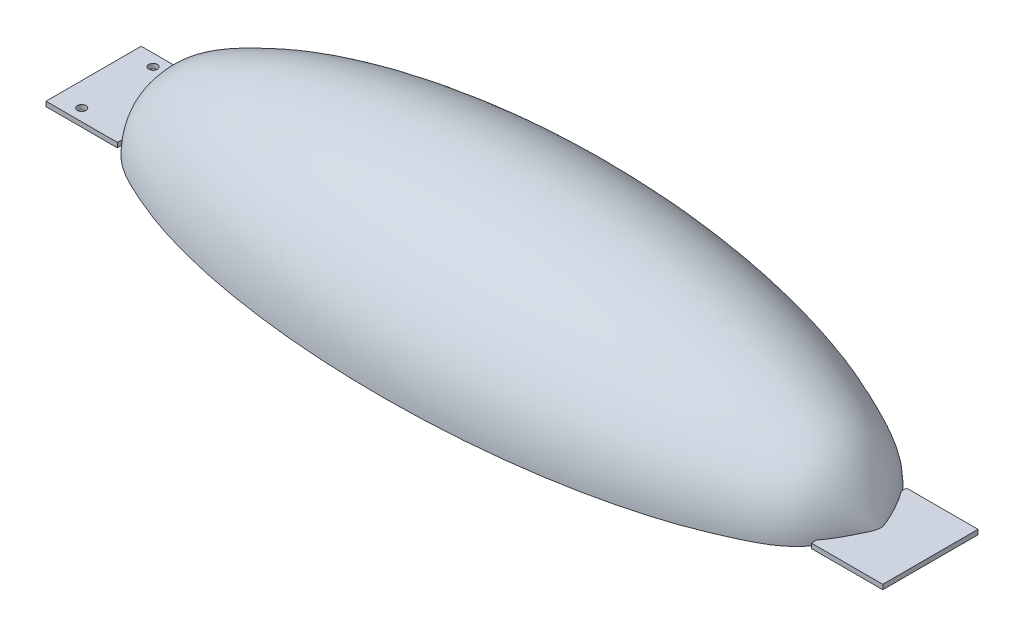
SolidWorks part; units mm, degrees
ref_plane "Front Plane" through (0, 0, 0) normal (0, 0, 1) x (1, 0, 0)
ref_plane "Top Plane" through (0, 0, 0) normal (0, 1, 0) x (1, 0, 0)
ref_plane "Right Plane" through (0, 0, 0) normal (1, 0, 0) x (0, 0, -1)
sketch "Sketch1" plane through (0, 0, 0) normal (0, 0, 1) x (1, 0, 0)
  line L0 (-311.5, 0) -> (0, 0)
  line L1 (10, 0) -> (-321.5, 0) construction
  spline S0 degree 3 poles (0, 0) (-4.2492, 8.9399) (-11.1739, 23.509) (-30.8102, 33.047) (-46.4415, 39.4769) (-62.1775, 44.1339) (-77.7886, 47.7571) (-93.3969, 50.5181) (-108.9899, 52.5683) (-124.5791, 53.9845) (-140.1651, 54.8169) (-155.75, 55.0915) (-171.3349, 54.8169) (-186.9209, 53.9845) (-202.5101, 52.5683) (-218.1031, 50.5181) (-233.7114, 47.7571) (-249.3225, 44.1339) (-265.0585, 39.4769) (-280.6898, 33.047) (-300.3261, 23.509) (-307.2508, 8.9399) (-311.5, 0) knots 0 0 0 0 0.082154 0.133883 0.182139 0.228907 0.274864 0.320327 0.365473 0.410415 0.455236 0.5 0.544764 0.589585 0.634527 0.679673 0.725136 0.771093 0.817861 0.866117 0.917846 1 1 1 1
revolve "Revolve1" add sketch "Sketch1" angle 360 about L1
sketch "Sketch2" plane through (0, 0, 0) normal (0, 1, 0) x (1, 0, 0)
  line L0 (-361.5, 80) -> (50, 80)
  line L1 (50, 80) -> (50, -80)
  line L2 (50, -80) -> (-361.5, -80)
  line L3 (-361.5, -80) -> (-361.5, 80)
extrude "Cut-Extrude1" cut sketch "Sketch2" against normal blind 80
sketch "Sketch3" plane through (0, 0, 0) normal (0, 1, 0) x (1, 0, 0)
  line L0 (-331.5, 20) -> (-301.5, 20)
  line L1 (-301.5, 20) -> (-301.5, -20)
  line L2 (-301.5, -20) -> (-331.5, -20)
  line L3 (-331.5, -20) -> (-331.5, 20)
  line L4 (-10, 20) -> (20, 20)
  line L5 (20, 20) -> (20, -20)
  line L6 (20, -20) -> (-10, -20)
  line L7 (-10, -20) -> (-10, 20)
extrude "Boss-Extrude1" add sketch "Sketch3" along normal blind 2
sketch "Sketch4" plane through (0, 0, 0) normal (0, 1, 0) x (1, 0, 0)
  circle A0 centre (-321.5, -15) radius 1.8
  circle A1 centre (-321.5, 15) radius 1.8
extrude "Cut-Extrude2" cut sketch "Sketch4" along normal blind 3
